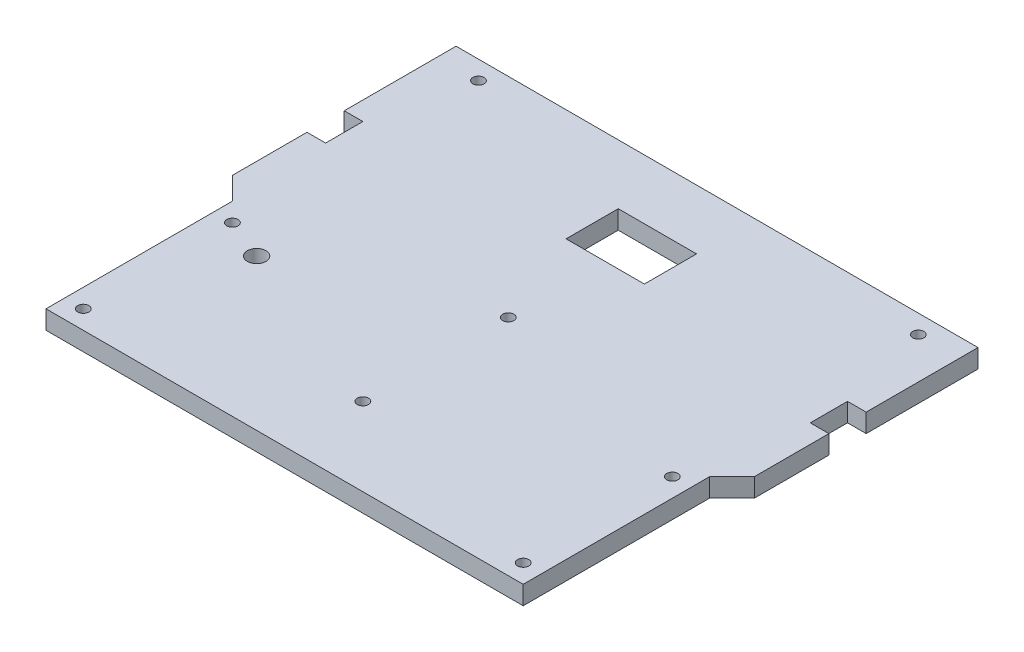
SolidWorks part; units mm, degrees
ref_plane "Front Plane" through (0, 0, 0) normal (0, 0, 1) x (1, 0, 0)
ref_plane "Top Plane" through (0, 0, 0) normal (0, 1, 0) x (1, 0, 0)
ref_plane "Right Plane" through (0, 0, 0) normal (1, 0, 0) x (0, 0, -1)
sketch "Sketch1" plane through (0, 0, 0) normal (0, 1, 0) x (1, 0, 0)
  line L31 (64, -116) -> (64, -66)
  line L32 (64, -66) -> (70, -60)
  line L34 (70, -60) -> (70, -40)
  line L35 (70, -40) -> (65, -40)
  line L36 (65, -40) -> (65, -30)
  line L37 (65, -30) -> (70, -30)
  line L38 (70, -30) -> (70, 0)
  line L39 (70, 0) -> (-70, 0)
  line L70 (0, 0) -> (0, -116) construction
  line L72 (-70, -30) -> (-70, 0)
  line L73 (-65, -30) -> (-70, -30)
  line L74 (-65, -40) -> (-65, -30)
  line L75 (-70, -40) -> (-65, -40)
  line L76 (-70, -60) -> (-70, -40)
  line L77 (-64, -66) -> (-70, -60)
  line L78 (-64, -116) -> (-64, -66)
  line L140 (-64, -116) -> (64, -116)
  circle A0 centre (59, -5) radius 1.5
  circle A1 centre (59, -71) radius 1.5
  circle A2 centre (59, -111) radius 1.5
  circle A3 centre (-59, -111) radius 1.5
  circle A4 centre (-59, -71) radius 1.5
  circle A5 centre (-59, -5) radius 1.5
  dimension "D30" = 3
  dimension "D1" = 70
  dimension "D2" = 30
  dimension "D4" = 5
  dimension "D5" = 20
  dimension "D6" = 6
  dimension "D7" = 135
  dimension "D8" = 10
  dimension "D25" = 50
  dimension "D31" = 5
  dimension "D33" = 5
  dimension "D34" = 5
  dimension "D9" = 5
extrude "Boss-Extrude1" add sketch "Sketch1" along normal blind 5
sketch "Sketch2" plane through (0, 5, 0) normal (0, 1, 0) x (1, 0, 0)
  line L0 (-64, -116) -> (64, -116) construction
  line L1 (38, -45) -> (-38, -45)
  line L2 (38, -45) -> (38, -106)
  line L3 (38, -106) -> (-38, -106)
  line L4 (-38, -45) -> (-38, -106)
  line L5 (0, -45) -> (0, -56) construction
  line L6 (10.5, -16) -> (-10.5, -16)
  line L7 (10.5, -16) -> (10.5, -30)
  line L8 (10.5, -30) -> (-10.5, -30)
  line L9 (-10.5, -16) -> (-10.5, -30)
  line L10 (0, -56) -> (0, -95) construction
  line L11 (0, -95) -> (0, -106) construction
  circle A0 centre (0, -56) radius 1.5
  circle A1 centre (0, -95) radius 1.5
  circle A2 centre (-48, -75.5) radius 2.5
  point P4 (0, -45)
  point P12 (0, -16)
  point P26 (-38, -75.5)
  dimension "D7" = 3
  dimension "D8" = 39
  dimension "D9" = 10
  dimension "D10" = 5
  dimension "D1" = 61
  dimension "D2" = 76
  dimension "D3" = 10
  dimension "D4" = 21
  dimension "D5" = 14
  dimension "D6" = 15
extrude "Cut-Extrude1" cut sketch "Sketch2" against normal through all contours L6 L9 L8 L7 | A0 | A1
equation "\"thick5mm\" = 5mm"
equation "\"D4@Sketch1\" = \"thick5mm\""
equation "\"hole\"= 0.3"
equation "\"D30@Sketch1\"=\"hole\""
equation "\"D1@Boss-Extrude1\" = \"thick5mm\""
